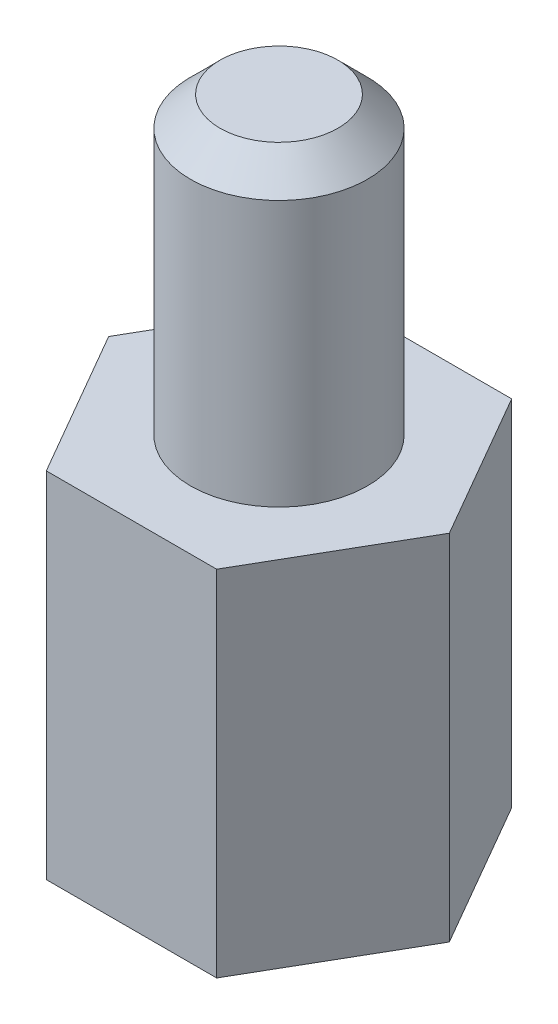
SolidWorks part; units mm, degrees
material "Латунь"
ref_plane "Спереди" through (0, 0, 0) normal (0, 0, 1) x (1, 0, 0)
ref_plane "Сверху" through (0, 0, 0) normal (0, 1, 0) x (1, 0, 0)
ref_plane "Справа" through (0, 0, 0) normal (1, 0, 0) x (0, 0, -1)
sketch "Эскиз1" plane through (0, 0, 0) normal (0, 1, 0) x (1, 0, 0)
  line L1 (1.4434, -2.5) -> (2.8868, 0)
  line L2 (2.8868, 0) -> (1.4434, 2.5)
  line L3 (1.4434, 2.5) -> (-1.4434, 2.5)
  line L4 (-1.4434, 2.5) -> (-2.8868, 0)
  line L5 (-2.8868, 0) -> (-1.4434, -2.5)
  line L6 (-1.4434, -2.5) -> (1.4434, -2.5)
  circle A0 centre (0, 0) radius 2.5 construction
  dimension "D1" = 5
extrude "Бобышка-Вытянуть1" add sketch "Эскиз1" along normal blind 6
hole_wizard "Диаметр отверстия Ø3.0 (3)1" positions "Эскиз2" profile "Эскиз3" hole size "Ø3.0" standard "Ansi Metric"
sketch "Эскиз2" plane through (0, 0, 0) normal (0, -1, 0) x (-1, 0, 0)
  point P0 (0, 0)
sketch "Эскиз3" plane through (0, 0, 0) normal (1, 0, 0) x (0, 0, -1)
  line L0 (0, 0) -> (0, 6.4013)
  line L1 (0, 6.4013) -> (1.5, 5.5)
  line L2 (1.5, 5.5) -> (1.5, 0)
  line L5 (1.5, 0) -> (0, 0)
  line L10 (0, 6.4013) -> (-1.5, 5.5) construction
  line L11 (0, -6.35) -> (0, 107.95) construction
  dimension "Диаметр отверстия" = 3
  dimension "Глубина отверстия" = 5.5
  dimension "Угол заточки сверла" = 118
sketch "Эскиз4" plane through (0, 6, 0) normal (0, 1, 0) x (1, 0, 0)
  circle A0 centre (0, 0) radius 1.5
  dimension "D1" = 3
extrude "Бобышка-Вытянуть2" add sketch "Эскиз4" along normal blind 5
cosmetic thread "Условное изображение резьбы1" parameters "D2"=2.439
chamfer "Фаска1" distance 0.5 angle 45 2 edges at (0, 11, 1.5) (0, 0, -1.5)
ref_point "Точка2"
